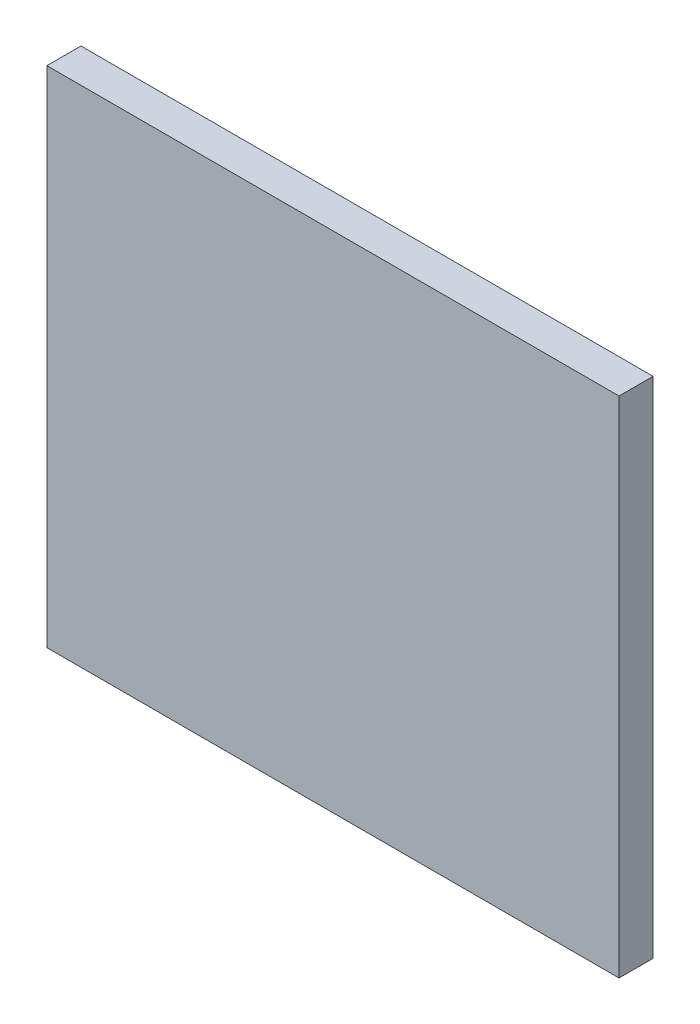
SolidWorks part; units mm, degrees
ref_plane "Alzado" through (0, 0, 0) normal (0, 0, 1) x (1, 0, 0)
ref_plane "Planta" through (0, 0, 0) normal (0, 1, 0) x (1, 0, 0)
ref_plane "Vista lateral" through (0, 0, 0) normal (1, 0, 0) x (0, 0, -1)
sketch "Croquis1" plane through (0, 0, 0) normal (0, 0, 1) x (1, 0, 0)
  line L1 (-184.5407, 150.8889) -> (-100.5407, 150.8889)
  line L2 (-184.5407, 150.8889) -> (-184.5407, 76.8889)
  line L3 (-184.5407, 76.8889) -> (-100.5407, 76.8889)
  line L4 (-100.5407, 150.8889) -> (-100.5407, 76.8889)
  dimension "D1" = 84
  dimension "D2" = 74
extrude "Saliente-Extruir1" add sketch "Croquis1" along normal blind 5
